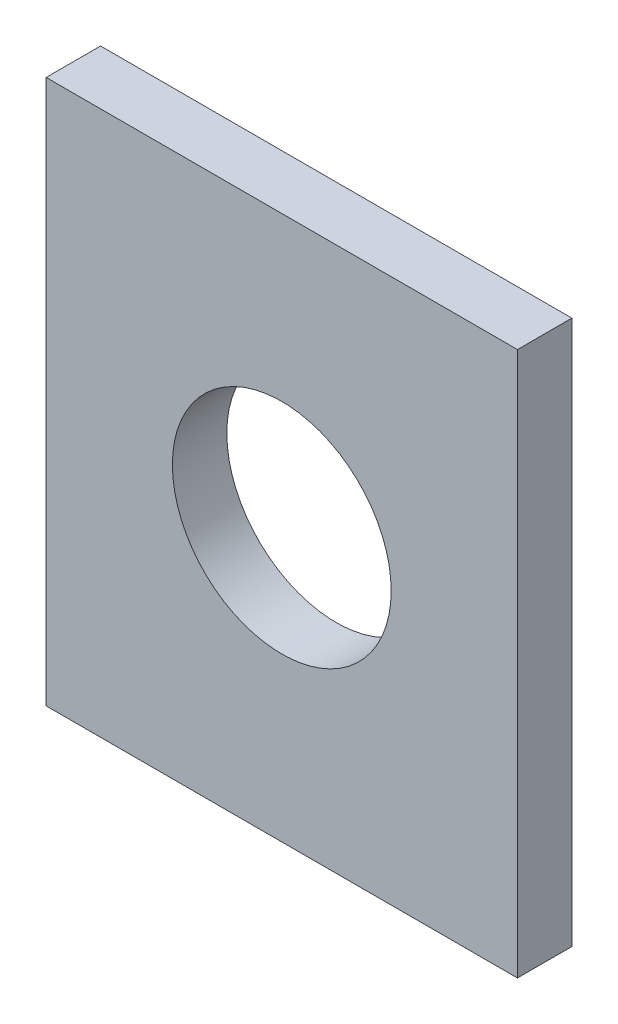
SolidWorks part; units mm, degrees
ref_plane "Front Plane" through (0, 0, 0) normal (0, 0, 1) x (1, 0, 0)
ref_plane "Top Plane" through (0, 0, 0) normal (0, 1, 0) x (1, 0, 0)
ref_plane "Right Plane" through (0, 0, 0) normal (1, 0, 0) x (0, 0, -1)
sketch "Sketch1" plane through (0, 0, 0) normal (0, 0, 1) x (1, 0, 0)
  line L1 (-10.9982, -12.7) -> (10.9982, -12.7)
  line L2 (-10.9982, -12.7) -> (-10.9982, 12.7)
  line L3 (-10.9982, 12.7) -> (10.9982, 12.7)
  line L4 (10.9982, -12.7) -> (10.9982, 12.7)
  line L5 (-10.9982, -12.7) -> (10.9982, 12.7) construction
  line L6 (-10.9982, 12.7) -> (10.9982, -12.7) construction
  circle A0 centre (0, 0) radius 5.1054
  point P0 (0, 0)
  dimension "D3" = 10.2108
  dimension "D1" = 25.4
  dimension "D2" = 21.9964
extrude "Boss-Extrude1" add sketch "Sketch1" along normal blind 2.54
